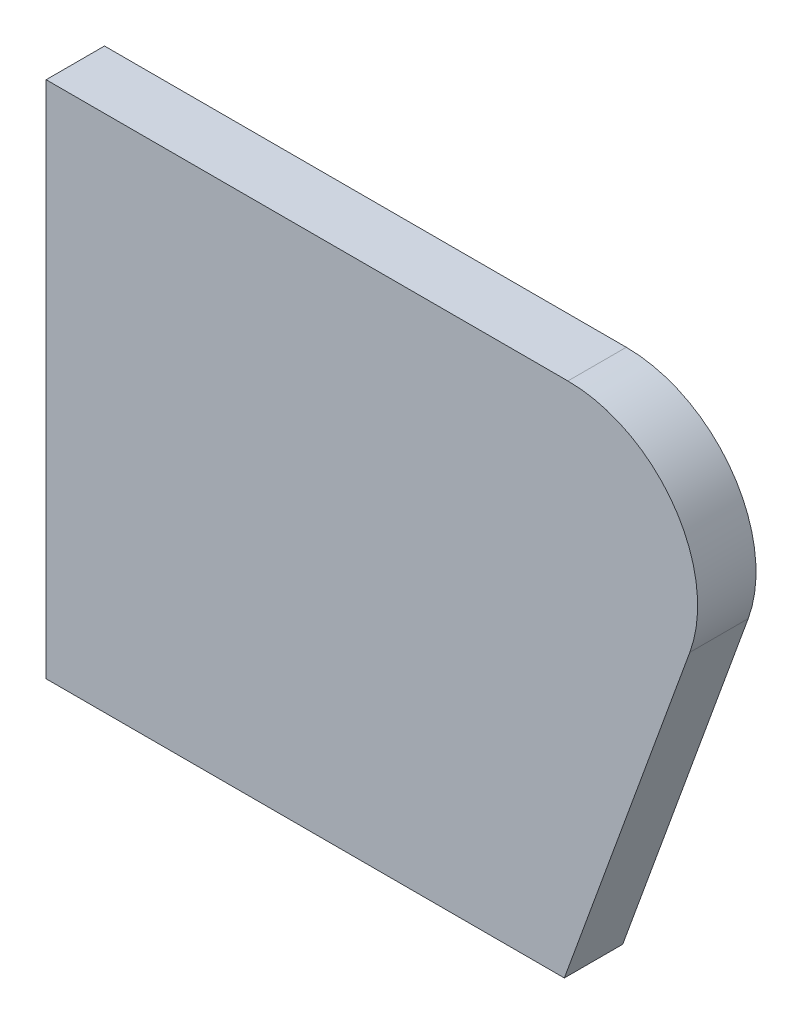
SolidWorks part; units mm, degrees
material "Glass"
ref_plane "Front Plane" through (0, 0, 0) normal (0, 0, 1) x (1, 0, 0)
ref_plane "Top Plane" through (0, 0, 0) normal (0, 1, 0) x (1, 0, 0)
ref_plane "Right Plane" through (0, 0, 0) normal (1, 0, 0) x (0, 0, -1)
sketch "Sketch1" plane through (0, 0, 0) normal (0, 0, 1) x (1, 0, 0)
  line L0 (-585.9297, 1301.2395) -> (-585.9297, -298.7547)
  line L1 (-585.9297, -298.7547) -> (1012.0603, -298.7547)
  line L2 (1012.0603, -298.7547) -> (1399.0284, 764.4314)
  line L3 (-585.9297, 1301.2395) -> (1023.1428, 1301.2395)
  arc A0 (1399.0284, 764.4314) -> (1023.1428, 1301.2395) centre (1023.1514, 901.2395) ccw
  dimension "D6" = 800
  dimension "D1" = 1597.99
  dimension "D2" = 1131.4189
  dimension "D3" = 110
  dimension "D4" = 1599.9942
  dimension "D5" = 1609.0725
extrude "Boss-Extrude1" add sketch "Sketch1" along normal blind 180
